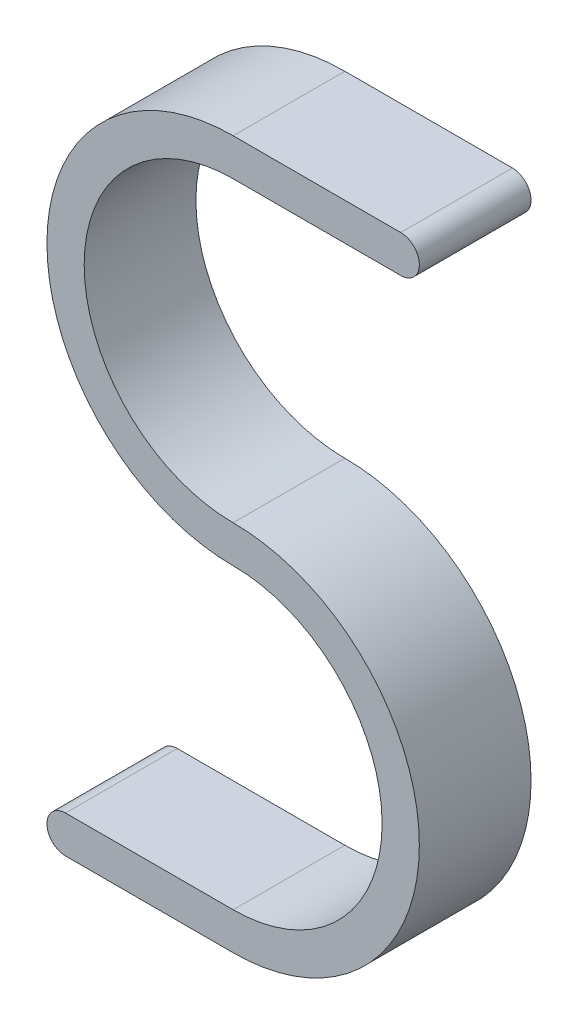
SolidWorks part; units mm, degrees
ref_plane "Front Plane" through (0, 0, 0) normal (0, 0, 1) x (1, 0, 0)
ref_plane "Top Plane" through (0, 0, 0) normal (0, 1, 0) x (1, 0, 0)
ref_plane "Right Plane" through (0, 0, 0) normal (1, 0, 0) x (0, 0, -1)
sketch "Sketch2" plane through (0, 0, 0) normal (0, 0, 1) x (1, 0, 0)
  line L0 (0, -40) -> (-22.5, -40)
  line L1 (0, 64.7767) -> (0, -49.4273) construction
  line L2 (0, 45) -> (22.5, 45)
  line L3 (0, 50) -> (22.5, 50)
  line L4 (22.5, 50) -> (22.5, 45) construction
  line L5 (0, -45) -> (-22.5, -45)
  line L6 (-22.5, -40) -> (-22.5, -45) construction
  arc A0 (0, 45) -> (0, 5) centre (0, 25) ccw
  arc A2 (0, 50) -> (0, 0) centre (0, 25) ccw
  arc A3 (22.5, 45) -> (22.5, 50) centre (22.5, 47.5) ccw
  arc A5 (0, -40) -> (0, 0) centre (0, -20) ccw
  arc A6 (0, -45) -> (0, 5) centre (0, -20) ccw
  arc A7 (-22.5, -40) -> (-22.5, -45) centre (-22.5, -42.5) ccw
  dimension "D1" = 22.5
  dimension "D2" = 22.5
  dimension "D3" = 40
  dimension "D4" = 25
  dimension "D5" = 20
  dimension "D6" = 25
  dimension "D7" = 20
  dimension "D8" = 22.5
  dimension "D9" = 50
extrude "Boss-Extrude1" add sketch "Sketch2" along normal blind 15
